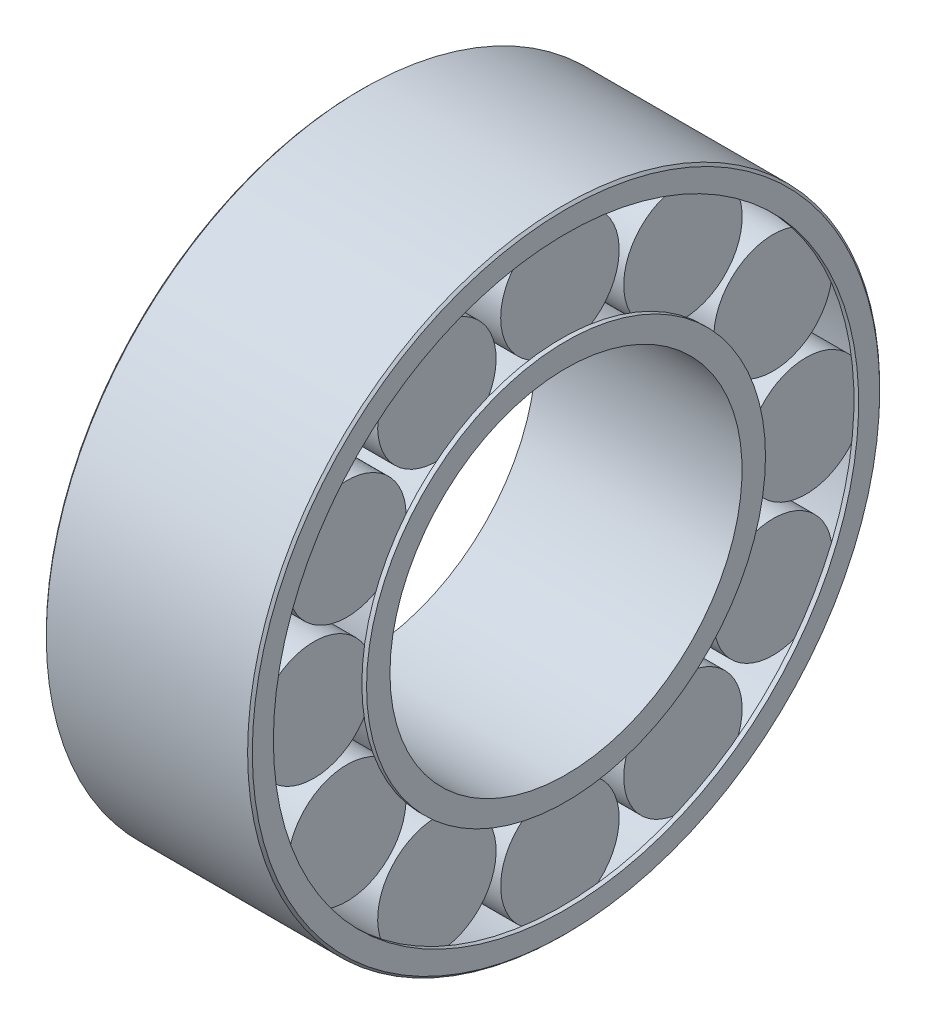
SolidWorks part; units mm, degrees
ref_plane "前视基准面" through (0, 0, 0) normal (0, 0, 1) x (1, 0, 0)
ref_plane "上视基准面" through (0, 0, 0) normal (0, 1, 0) x (1, 0, 0)
ref_plane "右视基准面" through (0, 0, 0) normal (1, 0, 0) x (0, 0, -1)
other "Configuration Table"
sketch "草图1" plane through (0, 0, 0) normal (0, 0, 1) x (1, 0, 0)
  line L0 (0, 0) -> (290.5743, 0) construction
  line L1 (0, 37.6) -> (44, 37.6)
  line L2 (0, 67.5) -> (44, 67.5)
  line L3 (0, 37.6) -> (0, 42.6)
  line L4 (0, 42.6) -> (1, 42.6)
  line L5 (1, 42.6) -> (1, 39.6)
  line L6 (1, 39.6) -> (43, 39.6)
  line L7 (43, 39.6) -> (43, 42.6)
  line L8 (43, 42.6) -> (44, 42.6)
  line L9 (44, 42.6) -> (44, 37.6)
  line L10 (0, 67.5) -> (0, 62.5)
  line L11 (0, 62.5) -> (1, 62.5)
  line L12 (1, 62.5) -> (1, 65.5)
  line L13 (1, 65.5) -> (43, 65.5)
  line L14 (43, 65.5) -> (43, 62.5)
  line L15 (43, 62.5) -> (44, 62.5)
  line L16 (44, 62.5) -> (44, 67.5)
  dimension "D1" = 44
  dimension "D2" = 75.2
  dimension "D3" = 135
  dimension "D4" = 1
  dimension "D5" = 2
  dimension "D6" = 3
  dimension "D7" = 2
revolve "旋转1" add sketch "草图1" angle 360 about L0
sketch "草图2" plane through (0, 0, 0) normal (0, 0, 1) x (1, 0, 0)
  line L1 (1.3, 65.2) -> (42.7, 65.2)
  line L2 (1.3, 65.2) -> (1.3, 52.55)
  line L3 (1.3, 39.9) -> (42.7, 39.9) construction
  line L4 (42.7, 65.2) -> (42.7, 52.55)
  line L5 (1.3, 65.2) -> (42.7, 39.9) construction
  line L6 (1.3, 39.9) -> (42.7, 65.2) construction
  line L7 (1, -65.5) -> (1, 65.5) construction
  line L8 (43, 39.6) -> (1, 39.6) construction
  line L9 (43, 65.5) -> (1, 65.5) construction
  line L10 (1.3, 52.55) -> (42.7, 52.55)
  line L11 (1.3, 52.55) -> (1.3, 39.9) construction
  line L12 (42.7, 39.9) -> (42.7, 52.55) construction
  line L13 (43, 65.5) -> (43, -65.5) construction
  point P0 (22, 52.55)
  dimension "D1" = 0.3
  dimension "D2" = 0.3
  dimension "D3" = 0.3
  dimension "D4" = 0.3
  dimension "D5" = 12.65
revolve "旋转2" add sketch "草图2" angle 360 about L10
pattern_circular "阵列(圆周)3" count 12 over 360 about axis through (0, 0, 0) along (1, 0, 0) of bodies 108
chamfer "倒角1" distance 0.5 angle 45 2 edges at (44, 0, 67.5) (0, 0, 67.5)
